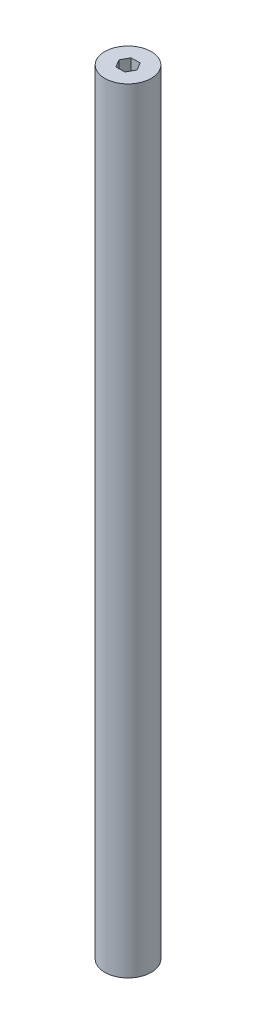
SolidWorks part; units mm, degrees
ref_plane "Front Plane" through (0, 0, 0) normal (0, 0, 1) x (1, 0, 0)
ref_plane "Top Plane" through (0, 0, 0) normal (0, 1, 0) x (1, 0, 0)
ref_plane "Right Plane" through (0, 0, 0) normal (1, 0, 0) x (0, 0, -1)
sketch "Sketch1" plane through (0, 0, 0) normal (0, 1, 0) x (1, 0, 0)
  line L1 (3.7705, -6.2886) -> (7.3313, 0.1211)
  line L2 (7.3313, 0.1211) -> (3.5608, 6.4097)
  line L3 (3.5608, 6.4097) -> (-3.7705, 6.2886)
  line L4 (-3.7705, 6.2886) -> (-7.3313, -0.1211)
  line L5 (-7.3313, -0.1211) -> (-3.5608, -6.4097)
  line L6 (-3.5608, -6.4097) -> (3.7705, -6.2886)
  circle A0 centre (0, 0) radius 19.05
  circle A1 centre (0, 0) radius 6.35 construction
  dimension "D1" = 38.1
  dimension "D2" = 12.7
extrude "Boss-Extrude1" add sketch "Sketch1" along normal blind 635
